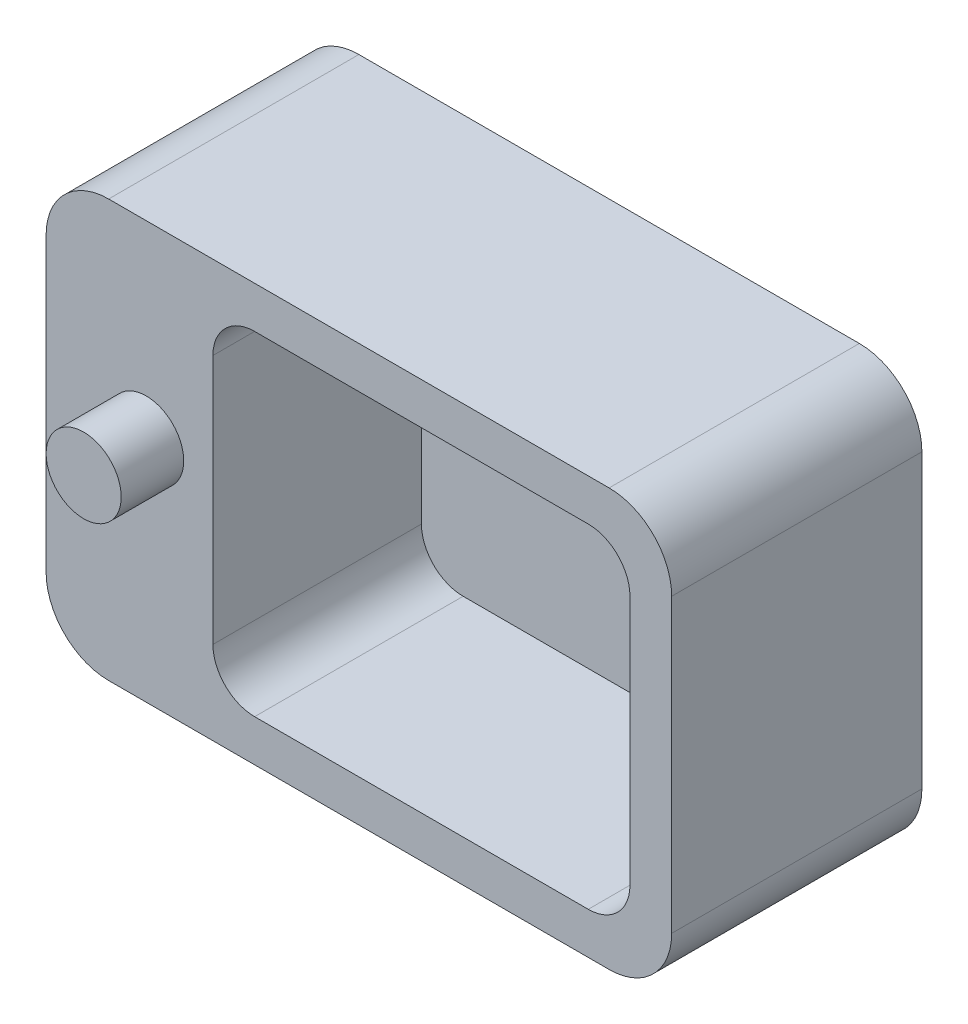
SolidWorks part; units mm, degrees
ref_plane "Plane1" through (0, 0, 0) normal (0, 0, 1) x (1, 0, 0)
ref_plane "Plane2" through (0, 0, 0) normal (0, 1, 0) x (1, 0, 0)
ref_plane "Plane3" through (0, 0, 0) normal (1, 0, 0) x (0, 0, -1)
sketch "Sketch1" plane through (0, 0, 0) normal (0, 0, 1) x (1, 0, 0)
  line L1 (15, 0) -> (135, 0)
  line L2 (0, 15) -> (0, 85)
  line L3 (15, 100) -> (135, 100)
  line L4 (150, 15) -> (150, 85)
  arc A0 (150, 15) -> (135, 0) centre (135, 15) cw
  arc A1 (150, 85) -> (135, 100) centre (135, 85) ccw
  arc A2 (15, 100) -> (0, 85) centre (15, 85) ccw
  arc A3 (0, 15) -> (15, 0) centre (15, 15) ccw
  point P7 (150, 0)
  point P12 (0, 100)
  point P15 (0, 0)
  dimension "D3" = 15
  dimension "D1" = 150
  dimension "D2" = 100
extrude "Base-Extrude" add sketch "Sketch1" along normal blind 60
sketch "Sketch2" plane through (0, 0, 60) normal (0, 0, 1) x (1, 0, 0)
  line L4 (15, 0) -> (135, 0) construction
  line L5 (150, 15) -> (150, 85) construction
  line L6 (135, 100) -> (15, 100) construction
  line L9 (40, 85) -> (40, 15)
  line L10 (40, 80) -> (40, 20)
  line L12 (140, 20) -> (140, 80)
  line L13 (130, 90) -> (50, 90)
  line L15 (50, 10) -> (130, 10)
  arc A4 (140, 20) -> (130, 10) centre (130, 20) cw
  arc A5 (130, 90) -> (140, 80) centre (130, 80) cw
  arc A6 (40, 20) -> (50, 10) centre (50, 20) ccw
  arc A7 (50, 90) -> (40, 80) centre (50, 80) ccw
  dimension "D1" = 10
  dimension "D6" = 10
  dimension "D2" = 10
  dimension "D3" = 10
  dimension "D4" = 10
  dimension "D5" = 40
extrude "Cut-Extrude1" cut sketch "Sketch2" against normal blind 50
sketch "Sketch3" plane through (0, 0, 60) normal (0, 0, 1) x (1, 0, 0)
  line L0 (0, 85) -> (0, 15) construction
  circle A1 centre (24, 54.61) radius 9
  dimension "D1" = 18
  dimension "D3" = 24
extrude "Boss-Extrude1" add sketch "Sketch3" along normal blind 15
